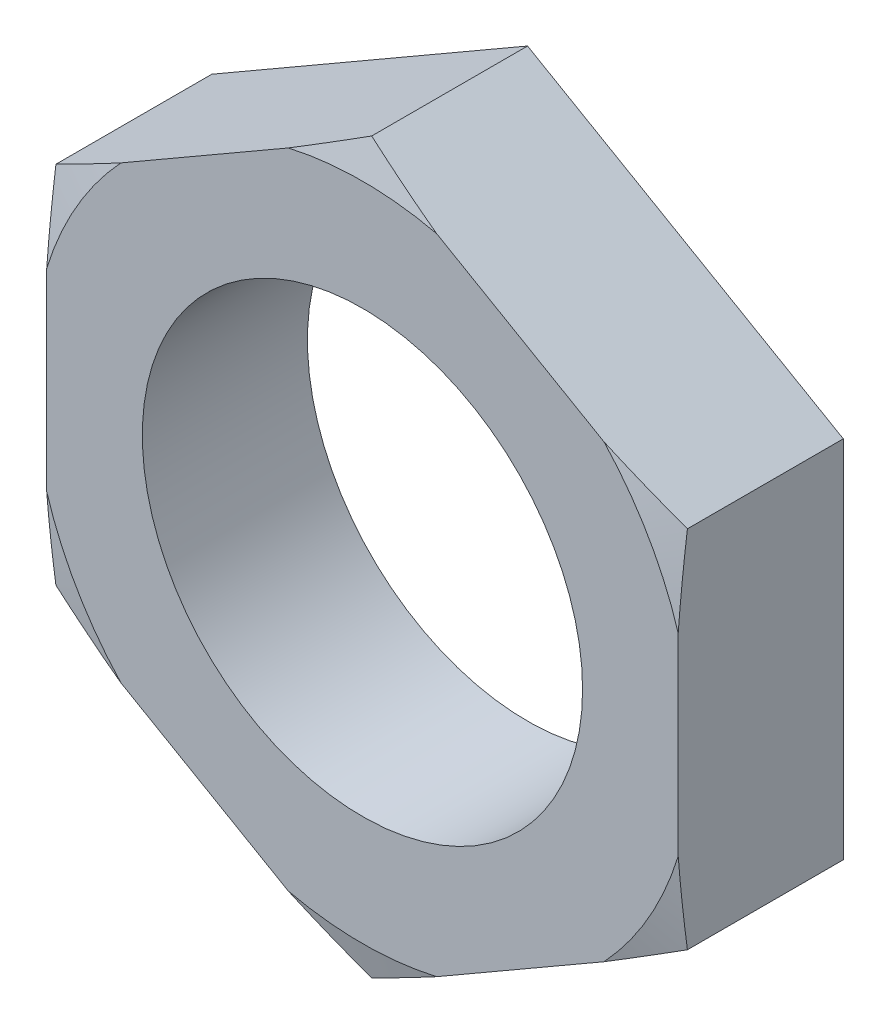
SolidWorks part; units mm, degrees
material "A3"
ref_plane "基准面1" through (0, 0, 0) normal (0, 0, 1) x (1, 0, 0)
ref_plane "基准面2" through (0, 0, 0) normal (0, 1, 0) x (1, 0, 0)
ref_plane "基准面3" through (0, 0, 0) normal (1, 0, 0) x (0, 0, -1)
sketch "尺寸草图" plane through (0, 0, 0) normal (0, 0, 1) x (1, 0, 0)
  line L0 (0, 0) -> (9.2444, 0)
  point P3 (8, 0)
  point P4 (3, 0)
  point P5 (12, 0)
  point P6 (5.1072, 0)
  point P7 (4.0801, 0)
  point P8 (13.25, 0)
  dimension "D" = 8
  dimension "e" = 13.25
  dimension "m" = 3
  dimension "s" = 12
sketch "草图1" plane through (0, 0, 0) normal (0, 0, 1) x (1, 0, 0)
  line L0 (0, 20.0172) -> (0, -14.298) construction
  line L1 (-13.2257, 0) -> (13.2257, 0) construction
  line L3 (0, 6.625) -> (-5.7374, 3.3125)
  line L4 (-5.7374, 3.3125) -> (-5.7374, -3.3125)
  line L5 (-5.7374, -3.3125) -> (0, -6.625)
  line L6 (0, -6.625) -> (5.7374, -3.3125)
  line L7 (5.7374, -3.3125) -> (5.7374, 3.3125)
  line L8 (5.7374, 3.3125) -> (0, 6.625)
  circle A0 centre (0, 0) radius 5.7374 construction
  circle A1 centre (0, 0) radius 4
  dimension "D" = 8
  dimension "e" = 13.25
extrude "基体-拉伸" add sketch "草图1" along normal blind 3
cosmetic thread "装饰螺纹线1"
chamfer "倒角1" [suppressed] distance 0.3333 angle 45
sketch "草图2" plane through (0, 0, 3) normal (0, 0, 1) x (1, 0, 0)
  circle A0 centre (0, 0) radius 6
  dimension "s" = 12
extrude "切除-拉伸1" cut sketch "草图2" against normal through all draft 75 flip side to cut
equation "\"D@草图1\" = \"D@尺寸草图\""
equation "\"m@基体-拉伸\" = \"m@尺寸草图\""
equation "\"e@草图1\" = \"e@尺寸草图\""
equation "\"s@草图2\" = \"s@尺寸草图\""
equation "\"D1@倒角1\" = \"D@草图1\"/24"
equation "\"D2@装饰螺纹线1\" = \"D@草图1\"-\"D@草图1\"/24"
